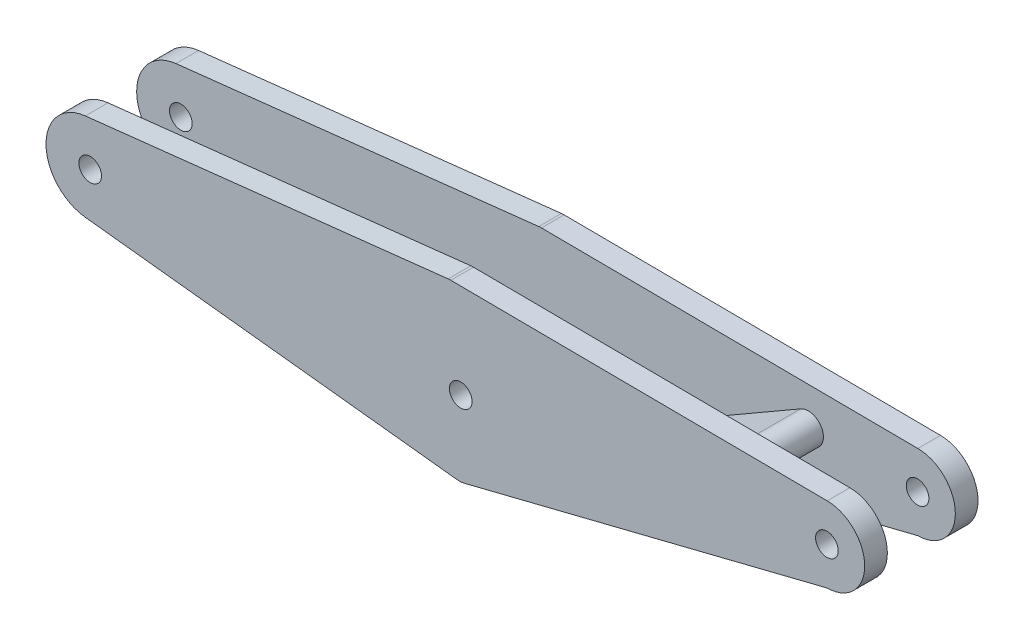
SolidWorks part; units mm, degrees
ref_plane "Front Plane" through (0, 0, 0) normal (0, 0, 1) x (1, 0, 0)
ref_plane "Top Plane" through (0, 0, 0) normal (0, 1, 0) x (1, 0, 0)
ref_plane "Right Plane" through (0, 0, 0) normal (1, 0, 0) x (0, 0, -1)
sketch "Sketch1" plane through (0, 0, 0) normal (0, 0, 1) x (1, 0, 0)
  line L4 (-147.3447, 6.6206) -> (-25.3551, 20.1674)
  line L5 (-24.4568, 20.2137) -> (102.0891, 19.262)
  line L6 (-147.3447, -22.9159) -> (-22.4812, -36.7818)
  line L7 (-19.7924, -36.6009) -> (102.0891, -6.1372)
  arc A2 (-147.3447, 6.6206) -> (-147.3447, -22.9159) centre (-145.7047, -8.1477) ccw
  arc A3 (102.0891, 19.262) -> (102.0891, -6.1372) centre (101.9936, 6.5624) cw
  circle A4 centre (-145.7047, -8.1477) radius 3.81
  circle A5 centre (101.9936, 6.5624) radius 3.81
  circle A6 centre (-21.1206, -11.5329) radius 3.81
  arc A7 (-22.4812, -36.7818) -> (-19.7924, -36.6009) centre (-21.6402, -29.2084) ccw
  arc A8 (-25.3551, 20.1674) -> (-24.4568, 20.2137) centre (-24.5141, 12.5939) cw
  point P14 (-21.1206, -36.9329)
  point P17 (-24.9073, 20.2171)
  dimension "D5" = 14.859
  dimension "D6" = 7.62
  dimension ".525" = 12.7
  dimension "D7" = 7.62
  dimension "D1" = 127
  dimension "D2" = 127
  dimension "D3" = 123.19
  dimension "D4" = 127
  dimension "D8" = 25.4
  dimension "D9" = 57.15
extrude "Boss-Extrude1" add sketch "Sketch1" against normal blind 38.1
sketch "Sketch2" plane through (0, 0, 0) normal (0, 1, 0) x (1, 0, 0)
  line L1 (123.2057, 30.48) -> (-173.4965, 30.48)
  line L2 (123.2057, 30.48) -> (123.2057, 7.62)
  line L3 (123.2057, 7.62) -> (-173.4965, 7.62)
  line L4 (-173.4965, 30.48) -> (-173.4965, 7.62)
  dimension "D1" = 7.62
  dimension "D2" = 7.62
extrude "Cut-Extrude1" cut sketch "Sketch2" against normal through all both and the other way through all
sketch "Sketch6" plane through (0, 0, -30.48) normal (0, 0, 1) x (1, 0, 0)
  line L0 (65.2591, 6.7165) -> (34.4633, -11.0635) construction
  line L1 (67.7991, 2.3171) -> (37.0033, -15.4629)
  line L2 (62.7191, 11.1159) -> (31.9233, -6.6641)
  line L3 (49.8612, -2.1735) -> (-0.9016, -2.1735) construction
  line L4 (-19.7924, -36.6009) -> (102.0891, -6.1372) construction
  arc A0 (67.7991, 2.3171) -> (62.7191, 11.1159) centre (65.2591, 6.7165) ccw
  arc A1 (31.9233, -6.6641) -> (37.0033, -15.4629) centre (34.4633, -11.0635) ccw
  point P2 (49.8612, -2.1735)
  dimension "D3" = 5.08
  dimension "D1" = 36.83
  dimension "D2" = 35.56
  dimension "D4" = 150
  dimension "D5" = 16.51
extrude "Boss-Extrude2" add sketch "Sketch6" along normal up to next
scale "Scale1" scale about centroid uniform scaling yes scale factor 2
